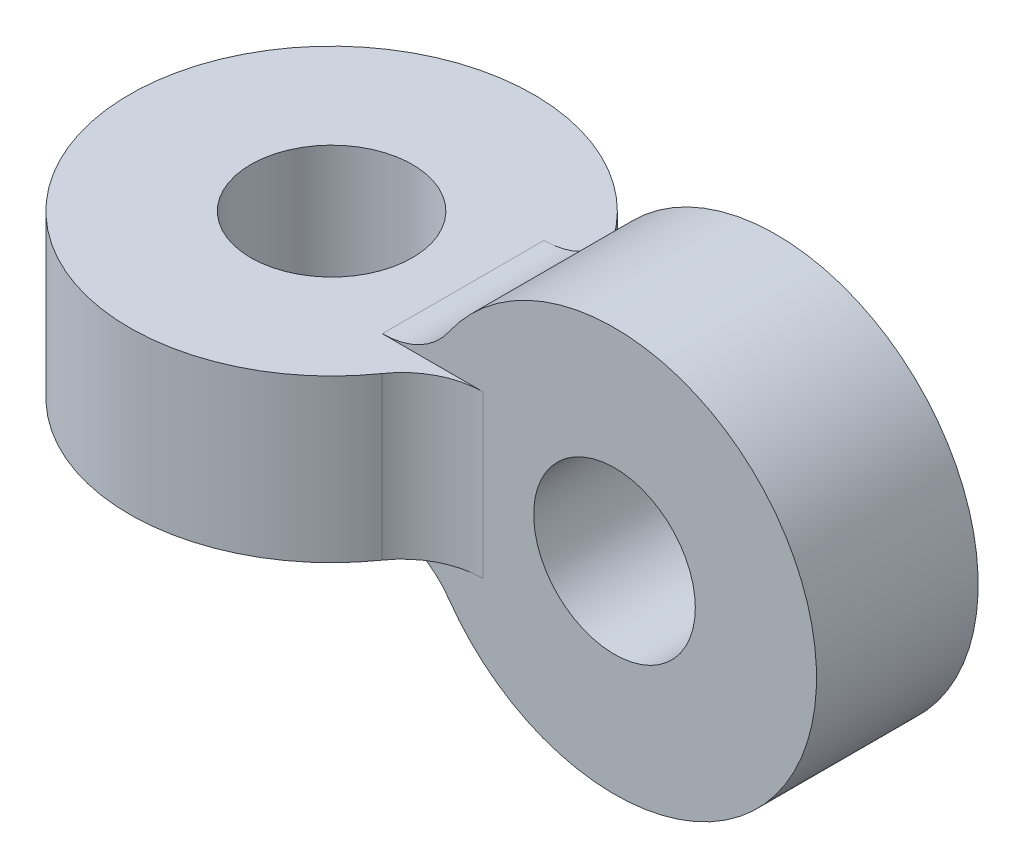
SolidWorks part; units mm, degrees
ref_plane "Front Plane" through (0, 0, 0) normal (0, 0, 1) x (1, 0, 0)
ref_plane "Top Plane" through (0, 0, 0) normal (0, 1, 0) x (1, 0, 0)
ref_plane "Right Plane" through (0, 0, 0) normal (1, 0, 0) x (0, 0, -1)
sketch "Sketch1" plane through (0, 0, 0) normal (0, 1, 0) x (1, 0, 0)
  circle A0 centre (0, 0) radius 1
  circle A1 centre (0, 0) radius 2.5
  dimension "D1" = 2
  dimension "D2" = 5
extrude "Boss-Extrude2" add sketch "Sketch1" along normal blind 2
sketch "Sketch2" plane through (0, 0, 0) normal (0, 0, 1) x (1, 0, 0)
  line L0 (2.5, 1) -> (4.5, 1) construction
  line L1 (2.5, 0) -> (2.5, 2) construction
  circle A0 centre (4.5, 1) radius 2.5
  circle A1 centre (4.5, 1) radius 1
  dimension "D2" = 2
  dimension "D3" = 5
  dimension "D1" = 2
extrude "Boss-Extrude3" add sketch "Sketch2" along normal mid plane 2
fillet "Fillet3" radius 1 1 edges at (2.2087, 2, 0)
fillet "Fillet4" radius 1 1 edges at (2.2087, 0, 0)
fillet "Fillet5" radius 1 1 edges at (2.2913, 1, -1)
fillet "Fillet8" radius 1 1 edges at (2.2913, 1, 1)
